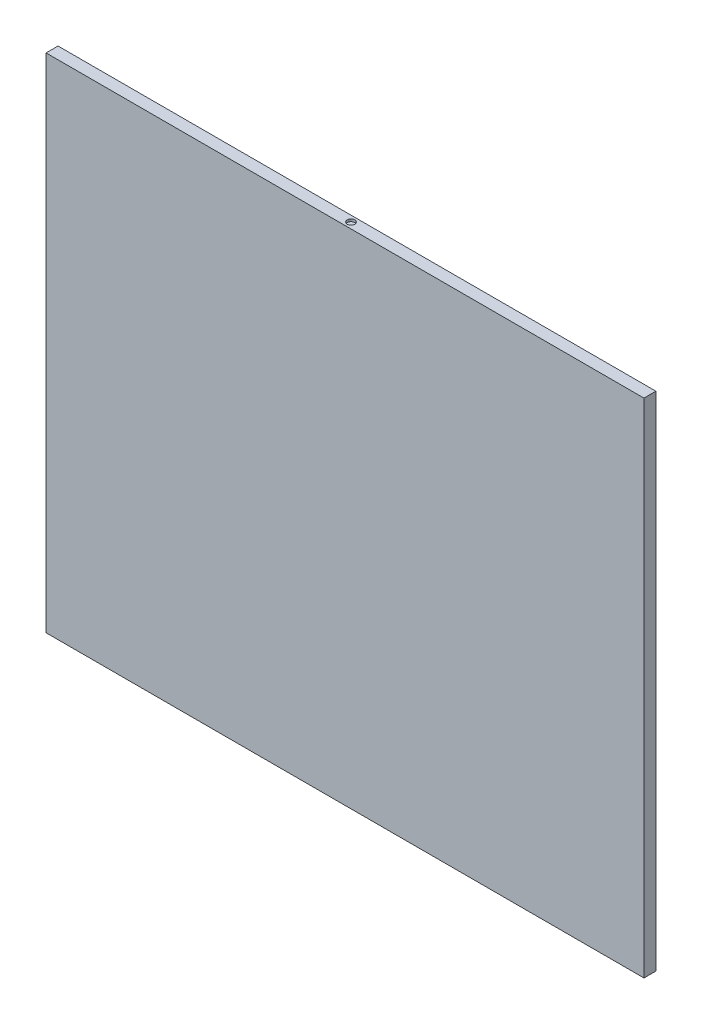
SolidWorks part; units mm, degrees
ref_plane "Plan de face" through (0, 0, 0) normal (0, 0, 1) x (1, 0, 0)
ref_plane "Plan de dessus" through (0, 0, 0) normal (0, 1, 0) x (1, 0, 0)
ref_plane "Plan de droite" through (0, 0, 0) normal (1, 0, 0) x (0, 0, -1)
sketch "Esquisse1" plane through (0, 0, 0) normal (0, 0, 1) x (1, 0, 0)
  line L1 (-125, -105) -> (125, -105)
  line L2 (-125, -105) -> (-125, 105)
  line L3 (-125, 105) -> (125, 105)
  line L4 (125, -105) -> (125, 105)
  line L5 (-125, -105) -> (125, 105) construction
  line L6 (-125, 105) -> (125, -105) construction
  point P0 (0, 0)
  dimension "D1" = 250
  dimension "D2" = 210
extrude "Boss.-Extru.1" add sketch "Esquisse1" along normal blind 5
sketch "Esquisse2" plane through (0, 105, 0) normal (0, 1, 0) x (1, 0, 0)
  line L0 (125, -5) -> (-125, 0) construction
  line L1 (-125, 0) -> (-125, -5)
  line L2 (-125, -5) -> (125, 0) construction
  line L3 (125, -5) -> (125, 0) construction
  line L4 (125, 0) -> (-125, 0) construction
  circle A0 centre (0, -2.5) radius 1.5874
  point P4 (0, -2.5)
extrude "Enlèv. mat.-Extru.2" cut sketch "Esquisse2" against normal blind 1 contours A0
